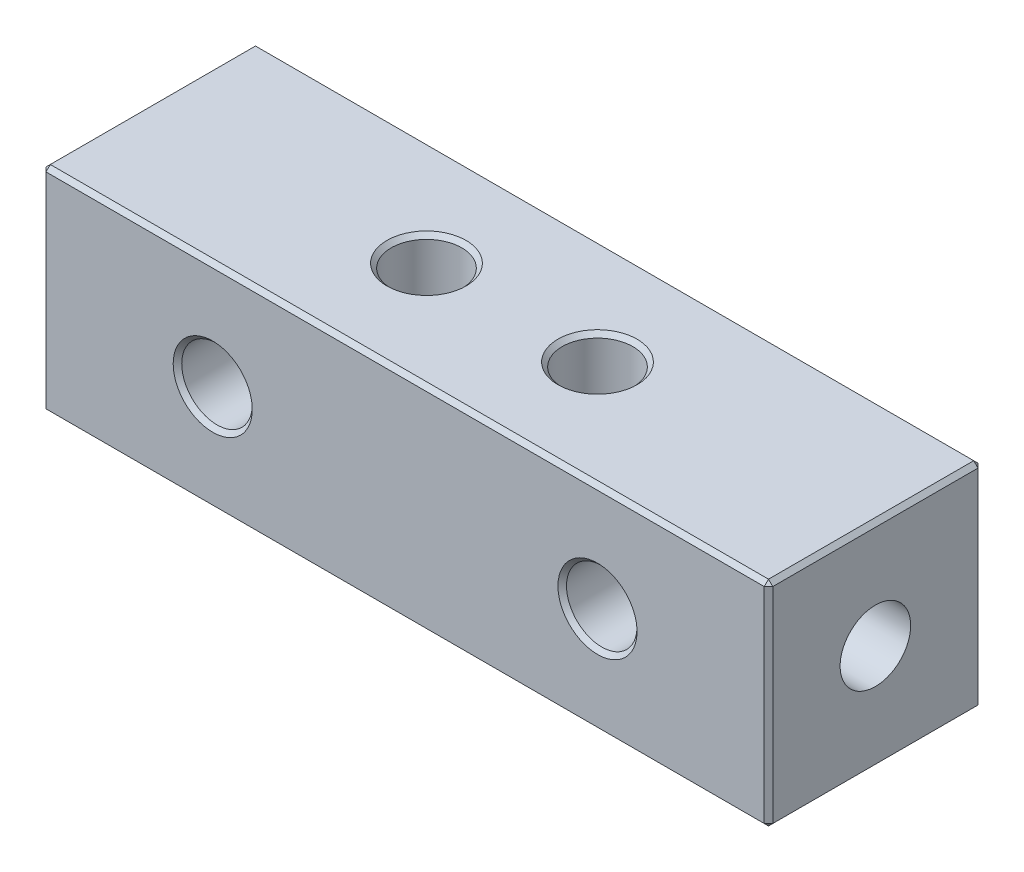
SolidWorks part; units mm, degrees
ref_plane "前视基准面" through (0, 0, 0) normal (0, 0, 1) x (1, 0, 0)
ref_plane "上视基准面" through (0, 0, 0) normal (0, 1, 0) x (1, 0, 0)
ref_plane "右视基准面" through (0, 0, 0) normal (1, 0, 0) x (0, 0, -1)
sketch "草图1" plane through (0, 0, 0) normal (0, 1, 0) x (1, 0, 0)
  line L1 (-17, 5) -> (17, 5)
  line L2 (-17, 5) -> (-17, -5)
  line L3 (-17, -5) -> (17, -5)
  line L4 (17, 5) -> (17, -5)
  line L5 (-17, 5) -> (17, -5) construction
  line L6 (-17, -5) -> (17, 5) construction
  point P0 (0, 0)
  dimension "D1" = 10
  dimension "D2" = 34
extrude "凸台-拉伸1" add sketch "草图1" along normal mid plane 10
hole_wizard "M4 螺纹孔1" positions "草图4" profile "草图6" tap size "M4" standard "GB" end condition through all
sketch "草图4" plane through (0, 5, 0) normal (0, 1, 0) x (1, 0, 0)
  line L0 (-17, 5) -> (-17, -5) construction
  line L1 (0, 0) -> (-50000, 0) construction
  point P0 (-4, 0)
  point P2 (4, 0)
  dimension "D1" = 13
  dimension "D2" = 8
sketch "草图6" plane through (-4, 5, 0) normal (1, 0, 0) x (0, 0, 1)
  line L0 (0, 0) -> (0, 10)
  line L1 (0, 10) -> (1.65, 10)
  line L2 (1.65, 10) -> (1.65, 0)
  line L5 (1.65, 0) -> (0, 0)
  line L11 (0, -6.35) -> (0, 107.95) construction
  dimension "通孔螺纹孔钻头直径" = 3.3
  dimension "通孔螺纹孔钻头深度" = 10
cosmetic thread "孔螺蚊线1" parameters "D2"=4
cosmetic thread "孔螺蚊线7" parameters "D2"=4
hole_wizard "M4 螺纹孔2" positions "草图7" profile "草图8" tap size "M4" standard "GB" end condition through all
sketch "草图7" plane through (0, 0, -5) normal (0, 0, -1) x (-1, 0, 0)
  line L0 (0, 0) -> (-50000, 0) construction
  line L1 (-17, 5) -> (-17, -5) construction
  point P0 (-9, 0)
  point P2 (9, 0)
  dimension "D1" = 8
  dimension "D2" = 18
sketch "草图8" plane through (9, 0, -5) normal (1, 0, 0) x (0, 1, 0)
  line L0 (0, 0) -> (0, 10)
  line L1 (0, 10) -> (1.65, 10)
  line L2 (1.65, 10) -> (1.65, 0)
  line L5 (1.65, 0) -> (0, 0)
  line L11 (0, -6.35) -> (0, 107.95) construction
  dimension "通孔螺纹孔钻头直径" = 3.3
  dimension "通孔螺纹孔钻头深度" = 10
cosmetic thread "孔螺蚊线3" parameters "D2"=4
cosmetic thread "孔螺蚊线4" parameters "D2"=4
chamfer "倒角1" distance 0.2 angle 45 20 edges at (4, -5, 1.65) (-4, -5, 1.65) (-10.65, 0, 5) (7.35, 0, 5) (4, 5, 1.65) (-4, 5, 1.65) (-17, -5, 0) (17, -5, 0) (-17, 0, 5) (0, -5, 5) (17, 0, 5) (0, 5, 5) (-17, 5, 0) (17, 5, 0) (17, 0, -5) (0, 5, -5) (-17, 0, -5) (0, -5, -5) (-10.65, 0, -5) (7.35, 0, -5)
hole_wizard "M4 螺纹孔3" positions "草图9" profile "草图10" tap size "M4" standard "GB"
sketch "草图9" plane through (-17, 0, 0) normal (-1, 0, 0) x (0, 0, 1)
  point P0 (0, 0)
sketch "草图10" plane through (-17, 0, 0) normal (0, 1, 0) x (0, 0, 1)
  line L0 (0, 0) -> (0, 6.35)
  line L1 (0, 6.35) -> (1.65, 6.35)
  line L2 (1.65, 6.35) -> (1.65, 0)
  line L5 (1.65, 0) -> (0, 0)
  line L11 (0, -6.35) -> (0, 107.95) construction
  dimension "通孔螺纹孔钻头直径" = 3.3
  dimension "通孔螺纹孔钻头深度" = 6.35
cosmetic thread "孔螺蚊线5" parameters "D2"=4
hole_wizard "M4 螺纹孔4" positions "草图11" profile "草图12" tap size "M4" standard "GB"
sketch "草图11" plane through (17, 0, 0) normal (1, 0, 0) x (0, 0, -1)
  point P0 (0, 0)
sketch "草图12" plane through (17, 0, 0) normal (0, 1, 0) x (0, 0, -1)
  line L0 (0, 0) -> (0, 6.35)
  line L1 (0, 6.35) -> (1.65, 6.35)
  line L2 (1.65, 6.35) -> (1.65, 0)
  line L5 (1.65, 0) -> (0, 0)
  line L11 (0, -6.35) -> (0, 107.95) construction
  dimension "通孔螺纹孔钻头直径" = 3.3
  dimension "通孔螺纹孔钻头深度" = 6.35
cosmetic thread "孔螺蚊线6" parameters "D2"=4
